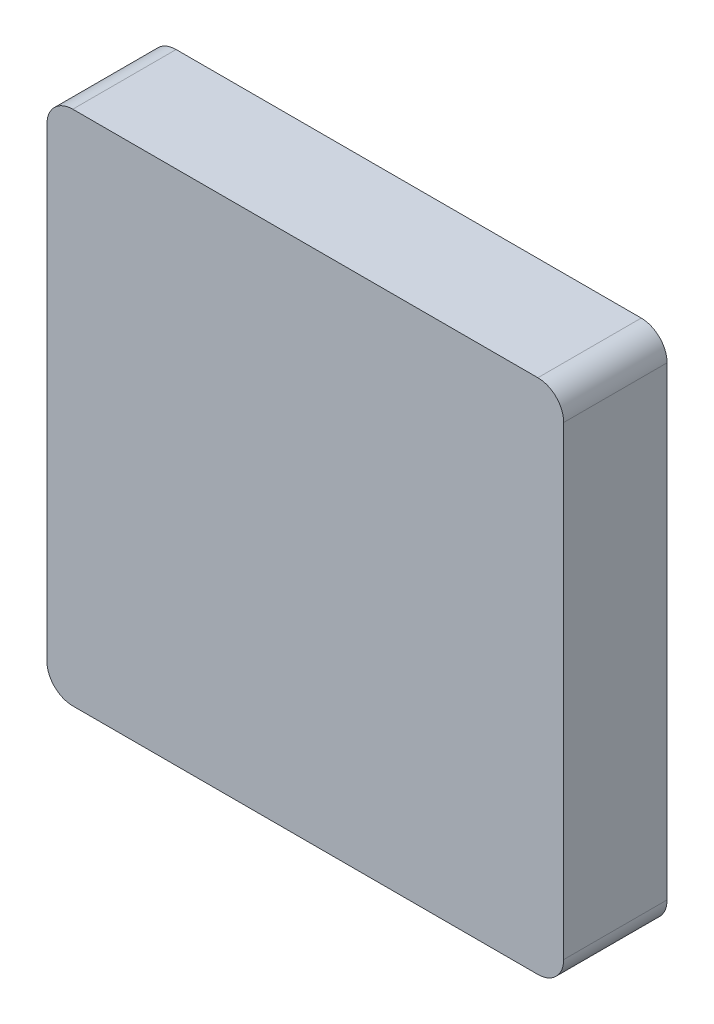
SolidWorks part; units mm, degrees
ref_plane "Front Plane" through (0, 0, 0) normal (0, 0, 1) x (1, 0, 0)
ref_plane "Top Plane" through (0, 0, 0) normal (0, 1, 0) x (1, 0, 0)
ref_plane "Right Plane" through (0, 0, 0) normal (1, 0, 0) x (0, 0, -1)
sketch "Sketch1" plane through (0, 0, 0) normal (0, 0, 1) x (1, 0, 0)
  line L1 (0, 0) -> (100, 0)
  line L2 (0, 0) -> (0, 100)
  line L3 (0, 100) -> (100, 100)
  line L4 (100, 0) -> (100, 100)
  dimension "D1" = 100
  dimension "D2" = 100
extrude "Boss-Extrude1" add sketch "Sketch1" along normal blind 20
fillet "Fillet1" radius 5 4 edges at (0, 100, 10) (0, 0, 10) (100, 0, 10) (100, 100, 10)
